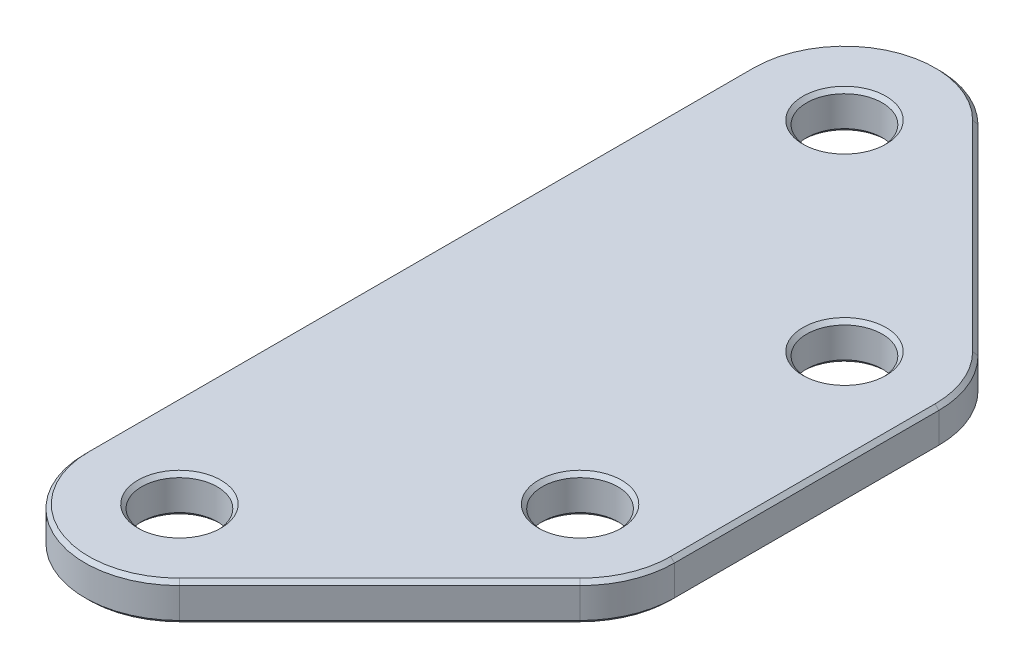
SolidWorks part; units mm, degrees
material "PMMA"
ref_plane "Front Plane" through (0, 0, 0) normal (0, 0, 1) x (1, 0, 0)
ref_plane "Top Plane" through (0, 0, 0) normal (0, 1, 0) x (1, 0, 0)
ref_plane "Right Plane" through (0, 0, 0) normal (1, 0, 0) x (0, 0, -1)
sketch "Sketch1" plane through (0, 0, 0) normal (0, 1, 0) x (1, 0, 0)
  line L0 (0, 0) -> (-100, 0) construction
  line L1 (-50, 176.066) -> (-50, -176.066) construction
  line L2 (-50, -176.066) -> (56.066, -70) construction
  line L3 (56.066, -70) -> (56.066, 70) construction
  line L4 (56.066, 70) -> (-50, 176.066) construction
  line L5 (-100, 176.066) -> (-100, -176.066)
  line L6 (-14.6447, -211.4214) -> (91.4214, -105.3553)
  line L7 (106.066, -70) -> (106.066, 70)
  line L8 (91.4214, 105.3553) -> (-14.6447, 211.4214)
  line L9 (56.066, -70) -> (139.4899, -104.5553) construction
  line L10 (56.066, 70) -> (143.1211, 106.0594) construction
  circle A0 centre (-50, 176.066) radius 20
  circle A1 centre (56.066, 70) radius 20
  circle A2 centre (56.066, -70) radius 20
  circle A3 centre (-50, -176.066) radius 20
  arc A4 (-100, -176.066) -> (-14.6447, -211.4214) centre (-50, -176.066) ccw
  arc A5 (91.4214, -105.3553) -> (106.066, -70) centre (56.066, -70) ccw
  arc A6 (106.066, 70) -> (91.4214, 105.3553) centre (56.066, 70) ccw
  arc A7 (-100, 176.066) -> (-14.6447, 211.4214) centre (-50, 176.066) cw
  point P12 (-50, 0)
  point P25 (106.066, -90.7107)
  point P28 (106.066, 90.7107)
  dimension "D3" = 40
  dimension "D4" = 40
  dimension "D5" = 40
  dimension "D6" = 40
  dimension "D15" = 50
  dimension "D1" = 135
  dimension "D2" = 135
  dimension "D7" = 150
  dimension "D8" = 140
  dimension "D9" = 50
  dimension "D10" = 225
  dimension "D11" = 225
  dimension "D12" = 50
  dimension "D13" = 112.5
  dimension "D14" = 112.5
extrude "Boss-Extrude1" add sketch "Sketch1" along normal blind 20
chamfer "Chamfer1" distance 2 angle 45 24 edges at (56.066, 0, -50) (56.066, 20, -50) (-50, 0, 196.066) (-50, 20, 196.066) (56.066, 0, 90) (56.066, 20, 90) (-50, 0, -156.066) (-50, 20, -156.066) (38.3883, 0, 158.3883) (102.26, 0, 89.1342) (106.066, 0, 0) (102.26, 0, -89.1342) (38.3883, 0, -158.3883) (-69.1342, 0, -222.26) (-100, 0, 0) (-69.1342, 0, 222.26) (-100, 20, 0) (-69.1342, 20, -222.26) (38.3883, 20, -158.3883) (102.26, 20, -89.1342) (106.066, 20, 0) (102.26, 20, 89.1342) (38.3883, 20, 158.3883) (-69.1342, 20, 222.26)
